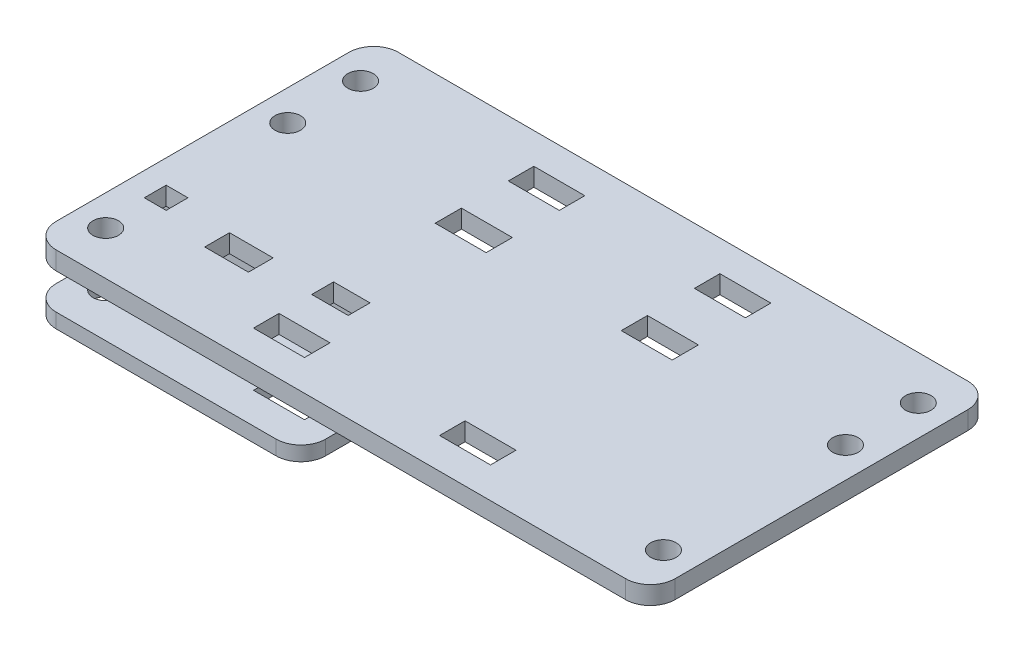
SolidWorks part; units mm, degrees
ref_plane "前视基准面" through (0, 0, 0) normal (0, 0, 1) x (1, 0, 0)
ref_plane "上视基准面" through (0, 0, 0) normal (0, 1, 0) x (1, 0, 0)
ref_plane "右视基准面" through (0, 0, 0) normal (1, 0, 0) x (0, 0, -1)
other "Configuration Table"
sketch "草图1" plane through (0, 0, 0) normal (0, 1, 0) x (1, 0, 0)
  line L0 (0, 0) -> (0, -23.5) construction
  line L1 (-42.5, -23.5) -> (42.5, -23.5)
  line L2 (-42.5, -23.5) -> (-42.5, 23.5)
  line L3 (-42.5, 23.5) -> (42.5, 23.5)
  line L4 (42.5, -23.5) -> (42.5, 23.5)
  line L5 (-42.5, -23.5) -> (42.5, 23.5) construction
  line L6 (-42.5, 23.5) -> (42.5, -23.5) construction
  line L7 (0, -23.5) -> (0, -17.5) construction
  line L8 (0, -17.5) -> (-38.3, -17.5) construction
  line L9 (-38.3, -17.5) -> (0, -17.5) construction
  line L10 (0, -17.5) -> (38.3, -17.5) construction
  line L11 (38.3, -17.5) -> (12.8, -17.5) construction
  line L12 (12.8, -17.5) -> (-38.3, -17.5) construction
  line L13 (-38.3, -17.5) -> (-12.75, -17.5) construction
  line L14 (-38.3, -17.5) -> (-38.3, 7.5) construction
  line L15 (38.3, -17.5) -> (38.3, 7.5) construction
  line L16 (-38.3, 7.5) -> (-38.3, 15.5) construction
  line L17 (38.3, 7.5) -> (38.3, 15.5) construction
  line L18 (-12.75, -17.5) -> (-12.75, 7.5) construction
  line L19 (-38.3, 7.5) -> (-38.3, 17.5) construction
  line L20 (38.3, 7.5) -> (38.3, 17.5) construction
  line L21 (12.8, -17.5) -> (12.8, 7.5) construction
  line L22 (12.8, 7.5) -> (12.8, 17.5) construction
  line L23 (12.8, 17.5) -> (-12.75, 17.5) construction
  line L25 (-16.25, -15.75) -> (-9.25, -15.75)
  line L26 (-16.25, -15.75) -> (-16.25, -19.25)
  line L27 (-16.25, -19.25) -> (-9.25, -19.25)
  line L28 (-9.25, -15.75) -> (-9.25, -19.25)
  line L29 (-16.25, -15.75) -> (-9.25, -19.25) construction
  line L30 (-16.25, -19.25) -> (-9.25, -15.75) construction
  line L31 (9.3, -15.75) -> (16.3, -15.75)
  line L32 (9.3, -15.75) -> (9.3, -19.25)
  line L33 (9.3, -19.25) -> (16.3, -19.25)
  line L34 (16.3, -15.75) -> (16.3, -19.25)
  line L35 (9.3, -15.75) -> (16.3, -19.25) construction
  line L36 (9.3, -19.25) -> (16.3, -15.75) construction
  line L37 (-16.25, 9.3) -> (-9.25, 9.3)
  line L38 (-16.25, 9.3) -> (-16.25, 5.7)
  line L39 (-16.25, 5.7) -> (-9.25, 5.7)
  line L40 (-9.25, 9.3) -> (-9.25, 5.7)
  line L41 (-16.25, 9.3) -> (-9.25, 5.7) construction
  line L42 (-16.25, 5.7) -> (-9.25, 9.3) construction
  line L43 (9.3, 9.3) -> (16.3, 9.3)
  line L44 (9.3, 9.3) -> (9.3, 5.7)
  line L45 (9.3, 5.7) -> (16.3, 5.7)
  line L46 (16.3, 9.3) -> (16.3, 5.7)
  line L47 (9.3, 9.3) -> (16.3, 5.7) construction
  line L48 (9.3, 5.7) -> (16.3, 9.3) construction
  line L49 (-16.25, 19.25) -> (-9.25, 19.25)
  line L50 (-16.25, 19.25) -> (-16.25, 15.75)
  line L51 (-16.25, 15.75) -> (-9.25, 15.75)
  line L52 (-9.25, 19.25) -> (-9.25, 15.75)
  line L53 (-16.25, 19.25) -> (-9.25, 15.75) construction
  line L54 (-16.25, 15.75) -> (-9.25, 19.25) construction
  line L55 (9.3, 19.25) -> (16.3, 19.25)
  line L56 (9.3, 19.25) -> (9.3, 15.75)
  line L57 (9.3, 15.75) -> (16.3, 15.75)
  line L58 (16.3, 19.25) -> (16.3, 15.75)
  line L59 (9.3, 19.25) -> (16.3, 15.75) construction
  line L60 (9.3, 15.75) -> (16.3, 19.25) construction
  circle A0 centre (-38.3, -17.5) radius 1.75
  circle A1 centre (38.3, -17.5) radius 1.75
  circle A2 centre (-38.3, 7.5) radius 1.75
  circle A3 centre (38.3, 7.5) radius 1.75
  circle A6 centre (-38.3, 17.5) radius 1.75
  circle A7 centre (38.3, 17.5) radius 1.75
  point P0 (0, 0)
  dimension "D8" = 3.5
  dimension "D9" = 3.5
  dimension "D11" = 25
  dimension "D12" = 3.5
  dimension "D13" = 3.5
  dimension "D16" = 10
  dimension "D17" = 3.5
  dimension "D19" = 3.5
  dimension "D1" = 47
  dimension "D2" = 85
  dimension "D3" = 6
  dimension "D4" = 38.3
  dimension "D5" = 38.3
  dimension "D6" = 25.5
  dimension "D7" = 25.55
  dimension "D10" = 25
  dimension "D14" = 8
  dimension "D15" = 8
  dimension "D18" = 25
  dimension "D20" = 25
  dimension "D21" = 10
  dimension "D22" = 3.5
  dimension "D23" = 7
  dimension "D24" = 3.5
  dimension "D25" = 7
  dimension "D26" = 3.6
  dimension "D27" = 3.6
  dimension "D28" = 7
  dimension "D29" = 3.5
  dimension "D30" = 7
extrude "凸台-拉伸1" add sketch "草图1" along normal blind 2.5
sketch "草图2" plane through (0, 0, 0) normal (0, 1, 0) x (1, 0, 0)
  line L0 (-38.3, -15.75) -> (-38.3, -5.75) construction
  line L1 (-38.3, -5.75) -> (-42.5, -5.75) construction
  line L2 (-42.5, 23.5) -> (-42.5, -23.5) construction
  line L4 (-42.5, -5.75) -> (-5.5, -5.75)
  line L5 (-42.5, -5.75) -> (-42.5, -2.75)
  line L6 (-42.5, -2.75) -> (-5.5, -2.75)
  line L7 (-5.5, -5.75) -> (-5.5, -2.75)
  circle A0 centre (-38.3, -17.5) radius 1.75 construction
  dimension "D1" = 10
  dimension "D2" = 3
  dimension "D3" = 37
extrude "凸台-拉伸2" add sketch "草图2" against normal blind 4.9
ref_plane "基准面1" through (0, -4.9, 0) normal (0, -1, 0) x (-1, 0, 0)
sketch "草图3" plane through (0, -4.9, 0) normal (0, -1, 0) x (-1, 0, 0)
  line L0 (36.55, -17.5) -> (40.05, -17.5) construction
  line L1 (5.5, -2.75) -> (42.5, -2.75)
  line L2 (5.5, -2.75) -> (5.5, -23.5)
  line L3 (5.5, -23.5) -> (42.5, -23.5)
  line L4 (42.5, -2.75) -> (42.5, -23.5)
  line L5 (9.25, -17.5) -> (16.25, -17.5) construction
  line L6 (9.25, -19.25) -> (9.25, -15.75) construction
  line L7 (16.25, -15.75) -> (16.25, -19.25) construction
  line L8 (16.25, -17.5) -> (12.75, -17.5) construction
  line L10 (9.25, -15.75) -> (16.25, -15.75)
  line L11 (9.25, -15.75) -> (9.25, -19.25)
  line L12 (9.25, -19.25) -> (16.25, -19.25)
  line L13 (16.25, -15.75) -> (16.25, -19.25)
  line L14 (9.25, -15.75) -> (16.25, -19.25) construction
  line L15 (9.25, -19.25) -> (16.25, -15.75) construction
  circle A0 centre (38.3, -17.5) radius 1.75 construction
  circle A1 centre (38.3, -17.5) radius 1.75
extrude "凸台-拉伸4" add sketch "草图3" along normal blind 2
fillet "圆角1" radius 3.4 6 edges at (-42.5, 1.25, -23.5) (42.5, 1.25, -23.5) (42.5, 1.25, 23.5) (-5.5, -5.9, 23.5) (-42.5, -5.9, 23.5) (-42.5, 1.25, 23.5)
sketch "草图4" plane through (0, -4.9, 0) normal (0, -1, 0) x (-1, 0, 0)
  line L0 (16.25, -15.75) -> (16.25, -11.25) construction
  line L1 (16.25, -11.25) -> (36.25, -11.25) construction
  line L2 (36.25, -11.25) -> (26.25, -11.25) construction
  line L4 (23.25, -9.55) -> (29.25, -9.55)
  line L5 (23.25, -9.55) -> (23.25, -12.95)
  line L6 (23.25, -12.95) -> (29.25, -12.95)
  line L7 (29.25, -9.55) -> (29.25, -12.95)
  line L8 (23.25, -9.55) -> (29.25, -12.95) construction
  line L9 (23.25, -12.95) -> (29.25, -9.55) construction
  line L10 (16.25, -11.25) -> (11.25, -11.25)
  line L11 (16.25, -11.25) -> (16.25, -8.25)
  line L12 (16.25, -8.25) -> (11.25, -8.25)
  line L13 (11.25, -11.25) -> (11.25, -8.25)
  line L14 (36.25, -11.25) -> (39.25, -11.25)
  line L15 (36.25, -11.25) -> (36.25, -8.25)
  line L16 (36.25, -8.25) -> (39.25, -8.25)
  line L17 (39.25, -11.25) -> (39.25, -8.25)
  dimension "D1" = 4.5
  dimension "D2" = 20
  dimension "D3" = 3.4
  dimension "D4" = 6
  dimension "D5" = 3
  dimension "D6" = 5
  dimension "D7" = 3
extrude "切除-拉伸1" cut sketch "草图4" against normal up to surface (7.4 mm away) up to face at (-12.75, 2.5, -17.5)
fillet "圆角2" radius 6 1 edges at (-24, 0, 2.75)
